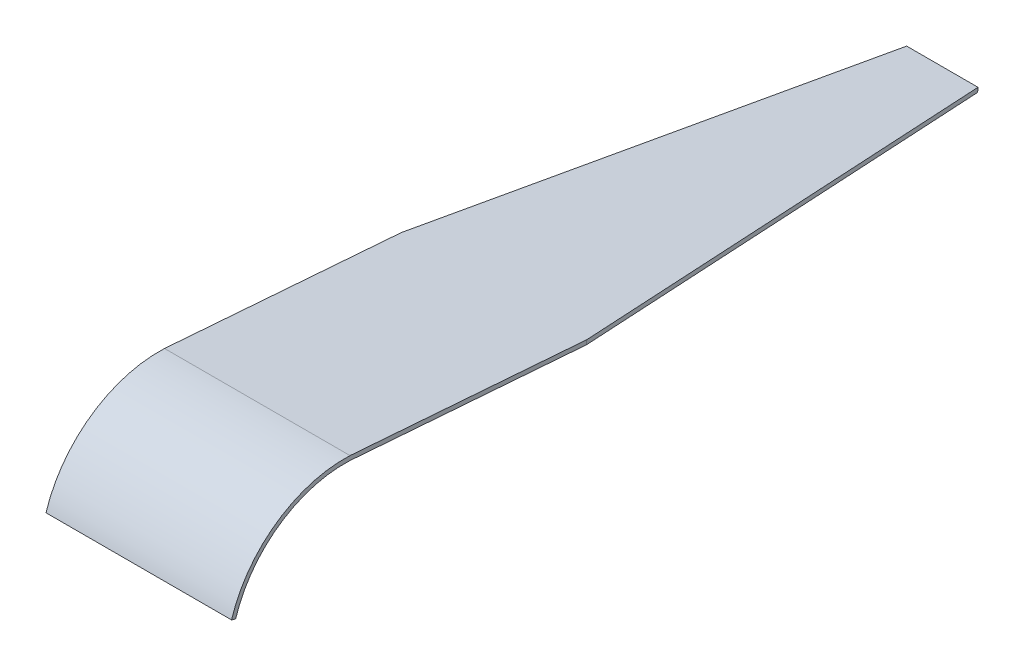
SolidWorks part; units mm, degrees
ref_plane "Front Plane" through (0, 0, 0) normal (0, 0, 1) x (1, 0, 0)
ref_plane "Top Plane" through (0, 0, 0) normal (0, 1, 0) x (1, 0, 0)
ref_plane "Right Plane" through (0, 0, 0) normal (1, 0, 0) x (0, 0, -1)
sketch "Sketch1" plane through (0, 0, 0) normal (1, 0, 0) x (0, 0, -1)
  line L0 (-106.3577, 0) -> (163.6423, 0) construction
  line L2 (173.6423, 9.798) -> (-66.3577, 28.0501)
  arc A0 (-106.3577, 0) -> (-66.3577, 28.0501) centre (-68.1715, -11.9088) cw
  dimension "D4" = 40
  dimension "D1" = 270
  dimension "D2" = 280
  dimension "D3" = 14
  dimension "D5" = 240
  dimension "D6" = 28.0501
extrude "Extrude-Thin2" add sketch "Sketch1" along normal blind 65 thin contours L2 A0
sketch "Sketch2" plane through (0, 24.367, -1.8531) normal (0, 0.9971, -0.0758) x (1, 0, 0)
  line L0 (20, 172.3993) -> (0, 14.8868)
  line L1 (65, 172.3993) -> (0, 172.3993) construction
  line L2 (0, 172.3993) -> (0, -68.3164) construction
  dimension "D1" = 20
  dimension "D4" = 122.4
sketch "Sketch4" plane through (0, 24.367, -1.8531) normal (0, 0.9971, -0.0758) x (1, 0, 0)
  line L0 (45, 172.3993) -> (65, 14.8868)
  line L1 (65, 172.3993) -> (0, 172.3993) construction
  line L2 (65, 172.3993) -> (65, -68.3164) construction
  dimension "D1" = 20
  dimension "D2" = 122.4
extrude "Cut-Extrude3" cut sketch "Sketch2" against normal through all and the other way through all flip side to cut contours L0
extrude "Cut-Extrude4" cut sketch "Sketch4" against normal through all and the other way through all contours L0
